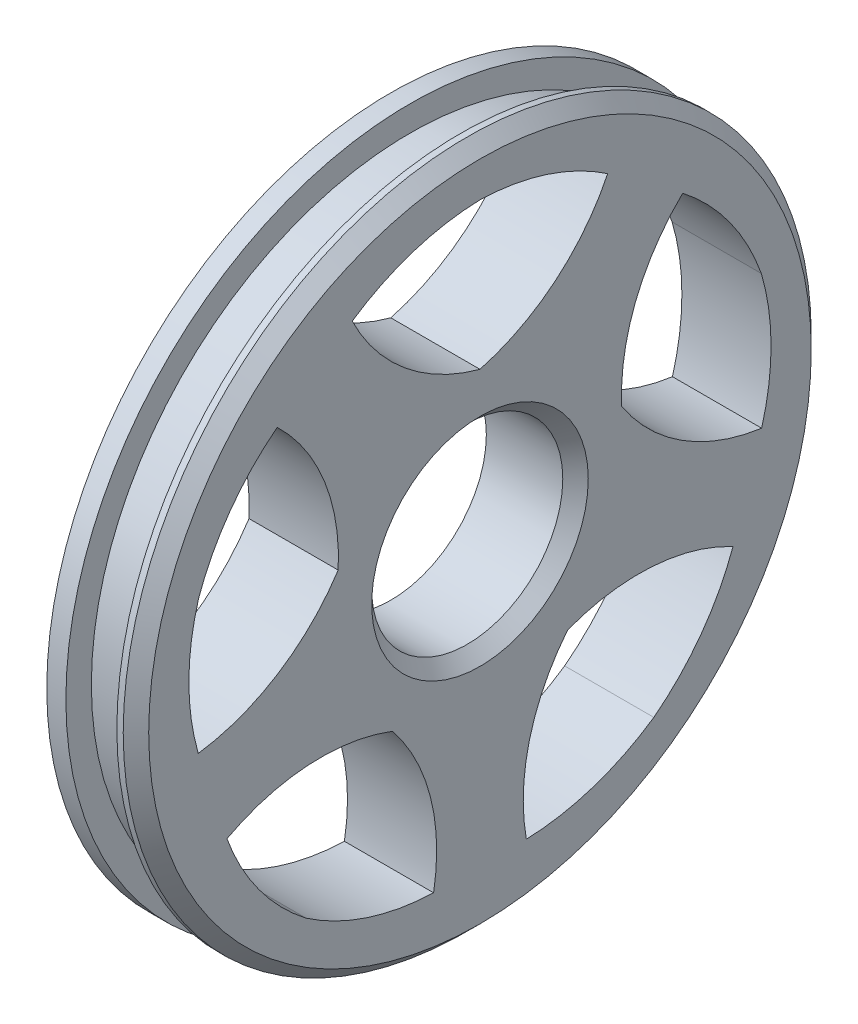
SolidWorks part; units mm, degrees
ref_plane "Front Plane" through (0, 0, 0) normal (0, 0, 1) x (1, 0, 0)
ref_plane "Top Plane" through (0, 0, 0) normal (0, 1, 0) x (1, 0, 0)
ref_plane "Right Plane" through (0, 0, 0) normal (1, 0, 0) x (0, 0, -1)
sketch "Sketch1" plane through (0, 0, 0) normal (1, 0, 0) x (0, 0, -1)
  circle A0 centre (0, 0) radius 13.5
  circle A1 centre (0, 0) radius 3.75
  dimension "D1" = 27
  dimension "D2" = 7.5
extrude "Boss-Extrude1" add sketch "Sketch1" along normal mid plane 3.5
sketch "Sketch2" plane through (0, 0, 0) normal (1, 0, 0) x (0, 0, -1)
  line L0 (0, 0) -> (0, 14.8201) construction
  arc A0 (0, 5.8497) -> (-5.0122, 9.994) centre (2.0377, 13.4173) cw
  arc A1 (-5.0122, 9.994) -> (0, 11.6087) centre (0.2591, 2.218) cw
  arc A2 (5.0122, 9.994) -> (0, 11.6087) centre (-0.2591, 2.218) ccw
  arc A3 (0, 5.8497) -> (5.0122, 9.994) centre (-2.0377, 13.4173) ccw
  point P11 (0, 4.9321)
  point P12 (0, 5.8497)
extrude "Cut-Extrude1" cut sketch "Sketch2" along normal through all both and the other way through all
pattern_circular "CirPattern1" count 5 over 360 about axis through (0, 0, 0) along (1, 0, 0) of "Cut-Extrude1"
chamfer "Chamfer1" distance 0.5 angle 45 2 edges at (1.75, 0, -13.5) (1.75, 0, -3.75)
sketch "Sketch4" plane through (0, 0, 0) normal (1, 0, 0) x (0, 0, -1)
  circle A0 centre (0, 0) radius 13.5
  circle A1 centre (0, 0) radius 12.5
  circle A2 centre (0, 0) radius 13.5 construction
  dimension "D1" = 1
extrude "Cut-Extrude3" cut sketch "Sketch4" against normal mid plane 2
equation "\"axis_diameter\"=5.66"
equation "\"padding\"=0.5"
